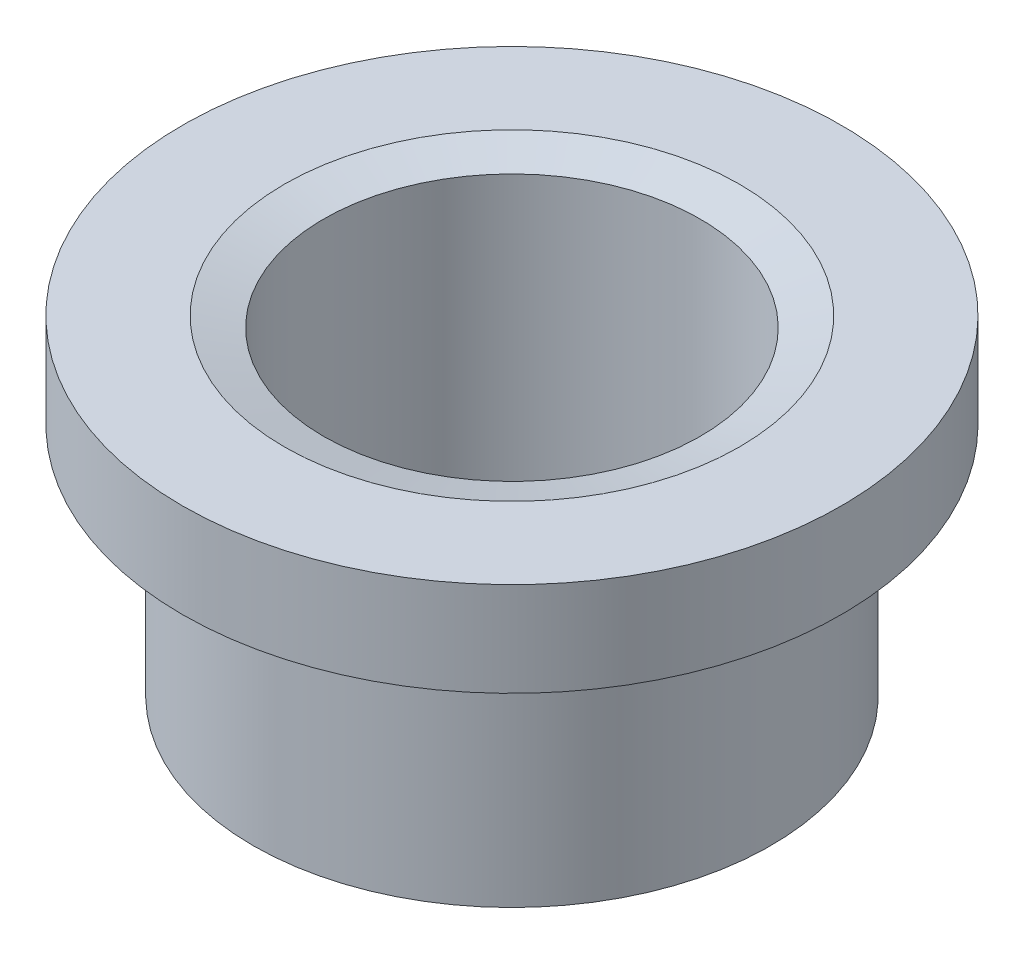
SolidWorks part; units mm, degrees
material "Brass"
ref_plane "Front Plane" through (0, 0, 0) normal (0, 0, 1) x (1, 0, 0)
ref_plane "Top Plane" through (0, 0, 0) normal (0, 1, 0) x (1, 0, 0)
ref_plane "Right Plane" through (0, 0, 0) normal (1, 0, 0) x (0, 0, -1)
sketch "Sketch1" plane through (0, 0, 0) normal (0, 1, 0) x (1, 0, 0)
  circle A0 centre (0, 0) radius 16.5
  dimension "D1" = 33
extrude "Boss-Extrude1" add sketch "Sketch1" along normal blind 15
sketch "Sketch2" plane through (0, 15, 0) normal (0, 1, 0) x (1, 0, 0)
  circle A0 centre (0, 0) radius 21
  dimension "D1" = 42
extrude "Boss-Extrude2" add sketch "Sketch2" along normal blind 6
sketch "Sketch3" plane through (0, 21, 0) normal (0, 1, 0) x (1, 0, 0)
  circle A0 centre (0, 0) radius 12
  dimension "D1" = 24
extrude "Cut-Extrude1" cut sketch "Sketch3" against normal through all
chamfer "Chamfer1" distance 2.5 angle 15 1 edges at (0, 21, 12)
